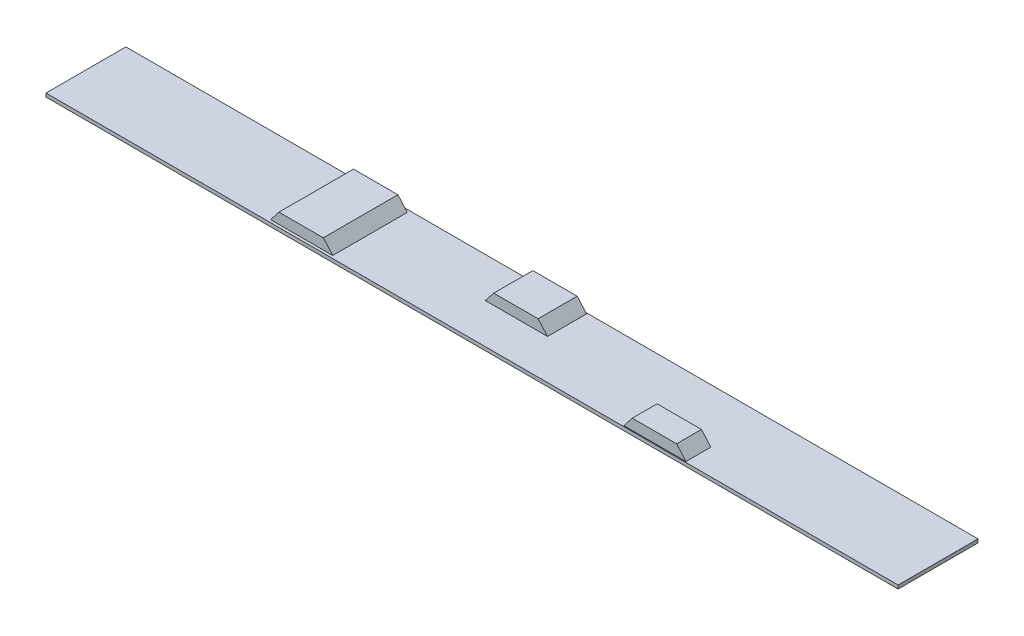
SolidWorks part; units mm, degrees
ref_plane "Front Plane" through (0, 0, 0) normal (0, 0, 1) x (1, 0, 0)
ref_plane "Top Plane" through (0, 0, 0) normal (0, 1, 0) x (1, 0, 0)
ref_plane "Right Plane" through (0, 0, 0) normal (1, 0, 0) x (0, 0, -1)
sketch "Sketch1" plane through (0, 0, 0) normal (0, 1, 0) x (1, 0, 0)
  line L1 (-1200, 112.5) -> (1200, 112.5)
  line L2 (-1200, 112.5) -> (-1200, -112.5)
  line L3 (-1200, -112.5) -> (1200, -112.5)
  line L4 (1200, 112.5) -> (1200, -112.5)
  line L5 (-1200, 112.5) -> (1200, -112.5) construction
  line L6 (-1200, -112.5) -> (1200, 112.5) construction
  point P0 (0, 0)
  dimension "D1" = 2400
  dimension "D2" = 225
extrude "Boss-Extrude1" add sketch "Sketch1" along normal blind 10
sketch "Sketch4" plane through (0, 0, 0) normal (0, 0, 1) x (1, 0, 0)
  line L0 (600, 10) -> (425, 10)
  line L1 (-1200, 10) -> (1200, 10) construction
  line L2 (1200, 10) -> (1200, 0) construction
  line L3 (600, 10) -> (573.6096, 40)
  line L4 (573.6096, 40) -> (448.6096, 40)
  line L5 (448.6096, 40) -> (425, 10)
  dimension "D1" = 175
  dimension "D2" = 600
  dimension "D3" = 125
  dimension "D4" = 30
extrude "Boss-Extrude2" add sketch "Sketch4" along normal blind 70 from offset 40
sketch "Sketch10" plane through (0, 0, 0) normal (0, 0, 1) x (1, 0, 0)
  line L0 (-75, 10) -> (100, 10)
  line L1 (-51.3904, 40) -> (-75, 10)
  line L2 (73.6096, 40) -> (-51.3904, 40)
  line L3 (100, 10) -> (73.6096, 40)
  line L4 (425, 10) -> (600, 10)
  line L5 (448.6096, 40) -> (425, 10)
  line L6 (573.6096, 40) -> (448.6096, 40)
  line L7 (600, 10) -> (573.6096, 40)
  line L8 (425, 10) -> (600, 10) construction
  line L9 (448.6096, 40) -> (425, 10) construction
  line L10 (573.6096, 40) -> (448.6096, 40) construction
  line L11 (600, 10) -> (573.6096, 40) construction
  dimension "D1" = 0
  dimension "D2" = 2
extrude "Boss-Extrude5" add sketch "Sketch10" against normal blind 110
sketch "Sketch11" plane through (0, 0, 0) normal (0, 0, 1) x (1, 0, 0)
  line L0 (-575, 10) -> (-400, 10)
  line L1 (-551.3904, 40) -> (-575, 10)
  line L2 (-426.3904, 40) -> (-551.3904, 40)
  line L3 (-400, 10) -> (-426.3904, 40)
  line L4 (425, 10) -> (600, 10)
  line L5 (448.6096, 40) -> (425, 10)
  line L6 (573.6096, 40) -> (448.6096, 40)
  line L7 (600, 10) -> (573.6096, 40)
  line L8 (425, 10) -> (600, 10) construction
  line L9 (448.6096, 40) -> (425, 10) construction
  line L10 (573.6096, 40) -> (448.6096, 40) construction
  line L11 (600, 10) -> (573.6096, 40) construction
  dimension "D1" = 0
  dimension "D2" = 2
extrude "Boss-Extrude6" add sketch "Sketch11" along normal mid plane 210
